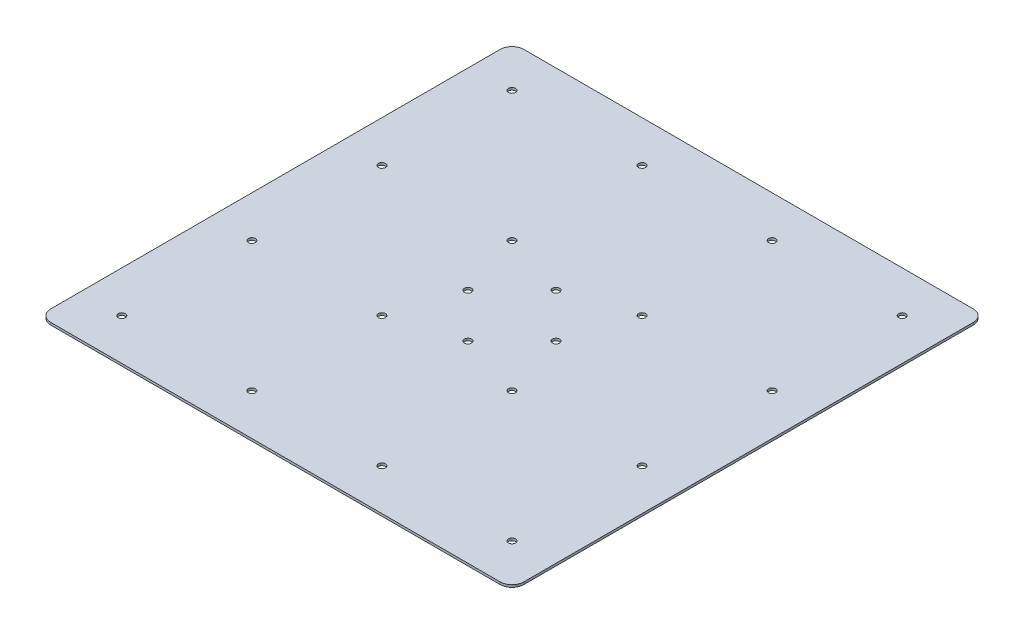
SolidWorks part; units mm, degrees
material "6063-O, Extruded Rod (SS)"
ref_plane "Front Plane" through (0, 0, 0) normal (0, 0, 1) x (1, 0, 0)
ref_plane "Top Plane" through (0, 0, 0) normal (0, 1, 0) x (1, 0, 0)
ref_plane "Right Plane" through (0, 0, 0) normal (1, 0, 0) x (0, 0, -1)
sketch "Sketch1" plane through (0, 0, 0) normal (0, 1, 0) x (1, 0, 0)
  line L1 (-200, 200) -> (200, 200)
  line L2 (-200, 200) -> (-200, -200)
  line L3 (-200, -200) -> (200, -200)
  line L4 (200, 200) -> (200, -200)
  line L5 (-200, 200) -> (200, -200) construction
  line L6 (-200, -200) -> (200, 200) construction
  point P0 (0, 0)
  dimension "D1" = 400
  dimension "D2" = 400
extrude "Boss-Extrude1" add sketch "Sketch1" along normal blind 2
sketch "Sketch3" plane through (0, 2, 0) normal (0, 1, 0) x (1, 0, 0)
  line L0 (0, 0) -> (-37.25, 0) construction
  line L1 (-19.25, 20.25) -> (19.25, 20.25)
  line L2 (-20.25, 19.25) -> (-20.25, -19.25)
  line L3 (-19.25, -20.25) -> (19.25, -20.25)
  line L4 (20.25, 19.25) -> (20.25, -19.25)
  line L5 (-20.25, 20.25) -> (20.25, -20.25) construction
  line L6 (-20.25, -20.25) -> (20.25, 20.25) construction
  line L7 (0, 0) -> (-37.25, 0) construction
  line L8 (0, 0) -> (0, 37.25) construction
  arc A0 (-20.25, -19.25) -> (-19.25, -20.25) centre (-19.25, -19.25) ccw
  arc A1 (19.25, -20.25) -> (20.25, -19.25) centre (19.25, -19.25) ccw
  arc A2 (19.25, 20.25) -> (20.25, 19.25) centre (19.25, 19.25) cw
  arc A3 (-19.25, 20.25) -> (-20.25, 19.25) centre (-19.25, 19.25) ccw
  circle A4 centre (-37.25, 0) radius 3
  circle A5 centre (0, 37.25) radius 3
  circle A6 centre (37.25, 0) radius 3
  circle A7 centre (0, -37.25) radius 3
  point P0 (0, 0)
  point P21 (-20.25, 0)
  dimension "D3" = 1
  dimension "D4" = 6
  dimension "D1" = 40.5
  dimension "D2" = 40.5
  dimension "D5" = 17
  dimension "D7" = 90
  dimension "D8" = 37.25
  dimension "D6" = 4
extrude "Cut-Extrude1" cut sketch "Sketch3" against normal through all contours A7 | A4 | A5 | A6
sketch "Sketch4" plane through (0, 2, 0) normal (0, 1, 0) x (1, 0, 0)
  line L0 (-165, 165) -> (-200, 165) construction
  line L1 (-200, 200) -> (-200, -200) construction
  line L2 (-165, 165) -> (-165, 200) construction
  line L3 (200, 200) -> (-200, 200) construction
  line L4 (-165, 165) -> (-55, 165) construction
  line L5 (-165, 165) -> (-165, 55) construction
  circle A0 centre (-165, 165) radius 3
  circle A1 centre (-55, 165) radius 3
  circle A2 centre (55, 165) radius 3
  circle A3 centre (165, 165) radius 3
  circle A4 centre (-55, 55) radius 3
  circle A5 centre (55, 55) radius 3
  circle A6 centre (165, 55) radius 3
  circle A7 centre (-55, -55) radius 3
  circle A8 centre (55, -55) radius 3
  circle A9 centre (165, -55) radius 3
  circle A10 centre (-55, -165) radius 3
  circle A11 centre (55, -165) radius 3
  circle A12 centre (165, -165) radius 3
  circle A13 centre (-165, 55) radius 3
  circle A14 centre (-165, -55) radius 3
  circle A15 centre (-165, -165) radius 3
  dimension "D2" = 6
  dimension "D1" = 35
  dimension "D5" = 90
  dimension "D6" = 110
  dimension "D7" = 110
  dimension "D3" = 4
  dimension "D4" = 4
extrude "Cut-Extrude2" cut sketch "Sketch4" against normal through all
fillet "Fillet1" radius 10 4 edges at (-200, 1, 200) (200, 1, 200) (200, 1, -200) (-200, 1, -200)
